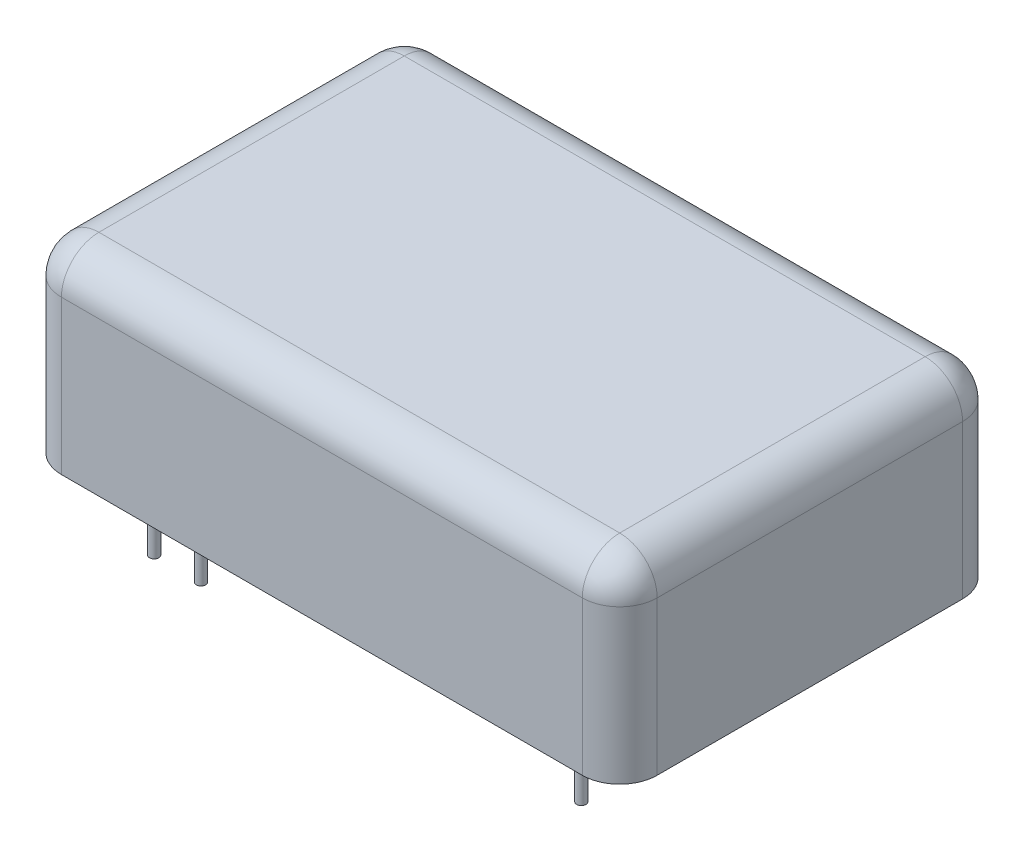
SolidWorks part; units mm, degrees
ref_plane "Спереди" through (0, 0, 0) normal (0, 0, 1) x (1, 0, 0)
ref_plane "Сверху" through (0, 0, 0) normal (0, 1, 0) x (1, 0, 0)
ref_plane "Справа" through (0, 0, 0) normal (1, 0, 0) x (0, 0, -1)
sketch "Эскиз1" plane through (0, 0, 0) normal (0, 1, 0) x (1, 0, 0)
  line L1 (-15.9, 10.15) -> (15.9, 10.15)
  line L2 (-15.9, 10.15) -> (-15.9, -10.15)
  line L3 (-15.9, -10.15) -> (15.9, -10.15)
  line L4 (15.9, 10.15) -> (15.9, -10.15)
  line L5 (-15.9, 10.15) -> (15.9, -10.15) construction
  line L6 (-15.9, -10.15) -> (15.9, 10.15) construction
  point P0 (0, 0)
  dimension "D1" = 20.3
  dimension "D2" = 31.8
extrude "Бобышка-Вытянуть1" add sketch "Эскиз1" along normal blind 10.2
sketch "Эскиз2" plane through (0, 0, 0) normal (0, -1, 0) x (1, 0, 0)
  line L0 (15.9, 10.15) -> (15.9, -10.15) construction
  line L1 (15.9, 0) -> (-15.9, 0) construction
  line L2 (-15.9, -10.15) -> (-15.9, 10.15) construction
  circle A0 centre (11.3, 7.6) radius 0.25
  circle A2 centre (-11.5, 7.6) radius 0.25
  circle A3 centre (-9, 7.6) radius 0.25
  circle A6 centre (-9, -7.6) radius 0.25
  circle A7 centre (-11.5, -7.6) radius 0.25
  circle A9 centre (11.3, -7.6) radius 0.25
  dimension "D1" = 0.5
  dimension "D3" = 0.5
  dimension "D4" = 0.5
  dimension "D9" = 20.3
  dimension "D10" = 4.6
  dimension "D12" = 7.6
  dimension "D13" = 7.6
  dimension "D15" = 7.6
  dimension "D6" = 2.5
extrude "Бобышка-Вытянуть2" add sketch "Эскиз2" along normal blind 3.8
fillet "Скругление1" radius 2 8 edges at (0, 10.2, 10.15) (-15.9, 10.2, 0) (0, 10.2, -10.15) (15.9, 10.2, 0) (15.9, 5.1, 10.15) (15.9, 5.1, -10.15) (-15.9, 5.1, -10.15) (-15.9, 5.1, 10.15)
sketch "Sketch1" plane through (0, 10.2, 0) normal (0, 1, 0) x (1, 0, 0)
  line L0 (-13.9, 8.15) -> (13.9, 8.15)
  line L1 (13.9, 8.15) -> (13.9, -8.15)
  line L2 (13.9, -8.15) -> (-13.9, -8.15)
  line L3 (-13.9, -8.15) -> (13.9, -8.15) construction
  line L4 (-13.9, 8.15) -> (-13.9, -8.15) construction
  line L5 (-13.9, -8.15) -> (-13.9, 8.15)
  circle A0 centre (-11.7159, -5.858) radius 0.7718
  text T0 "aimtec"
